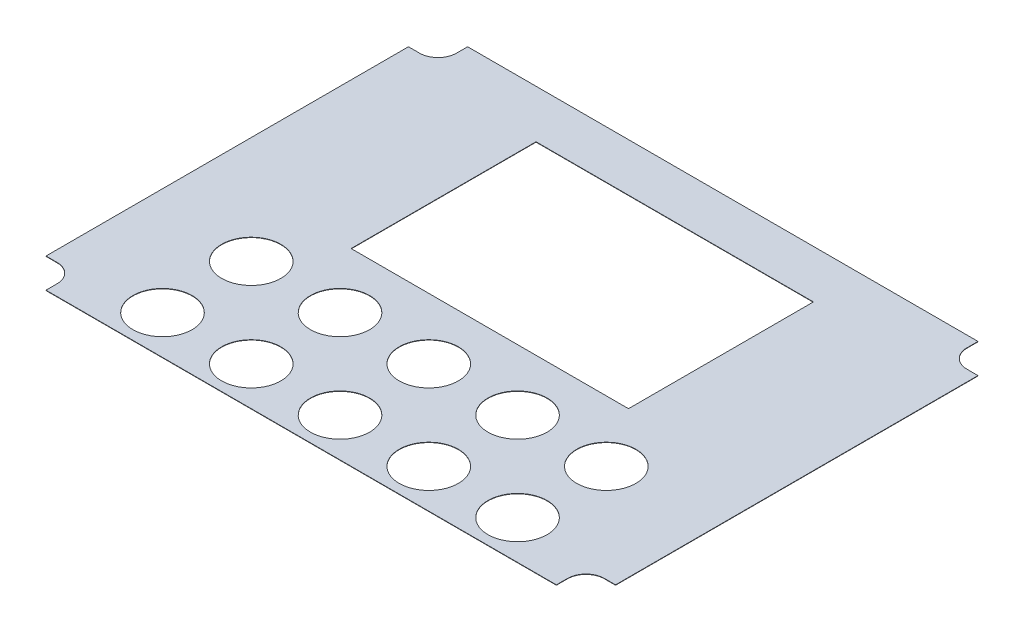
SolidWorks part; units mm, degrees
ref_plane "Front Plane" through (0, 0, 0) normal (0, 0, 1) x (1, 0, 0)
ref_plane "Top Plane" through (0, 0, 0) normal (0, 1, 0) x (1, 0, 0)
ref_plane "Right Plane" through (0, 0, 0) normal (1, 0, 0) x (0, 0, -1)
sketch "Sketch1" plane through (0, 0, 0) normal (0, 1, 0) x (1, 0, 0)
  line L1 (-77, 57) -> (77, 57)
  line L2 (-77, 57) -> (-77, -57)
  line L3 (-77, -57) -> (77, -57)
  line L4 (77, 57) -> (77, -57)
  line L5 (-77, 57) -> (77, -57) construction
  line L6 (-77, -57) -> (77, 57) construction
  point P0 (0, 0)
  dimension "D1" = 154
  dimension "D2" = 114
extrude "Boss-Extrude1" add sketch "Sketch1" along normal blind 0.1
sketch "Sketch2" plane through (0, 0.1, 0) normal (0, 1, 0) x (1, 0, 0)
  line L0 (-52.05, -19.4834) -> (-52.05, -25.5166)
  line L1 (-43.95, -19.4834) -> (-43.95, -25.5166)
  line L2 (-19.95, -19.4834) -> (-19.95, -25.5166)
  line L3 (-28.05, -19.4834) -> (-28.05, -25.5166)
  line L4 (4.05, -19.4834) -> (4.05, -25.5166)
  line L5 (-4.05, -19.4834) -> (-4.05, -25.5166)
  line L6 (28.05, -19.4834) -> (28.05, -25.5166)
  line L7 (19.95, -19.4834) -> (19.95, -25.5166)
  line L8 (52.05, -19.4834) -> (52.05, -25.5166)
  line L9 (43.95, -19.4834) -> (43.95, -25.5166)
  line L10 (-19.95, -43.4834) -> (-19.95, -49.5166)
  line L11 (-28.05, -43.4834) -> (-28.05, -49.5166)
  line L12 (4.05, -43.4834) -> (4.05, -49.5166)
  line L13 (-4.05, -43.4834) -> (-4.05, -49.5166)
  line L14 (28.05, -43.4834) -> (28.05, -49.5166)
  line L15 (19.95, -43.4834) -> (19.95, -49.5166)
  line L16 (52.05, -43.4834) -> (52.05, -49.5166)
  line L17 (43.95, -43.4834) -> (43.95, -49.5166)
  line L18 (-43.95, -43.4834) -> (-43.95, -49.5166)
  line L19 (-52.05, -43.4834) -> (-52.05, -49.5166)
  line L20 (-80.6235, 55.25) -> (97.5881, 55.25) construction
  line L21 (-86.1798, -55.25) -> (90.3856, -55.25) construction
  circle A0 centre (-60, 45) radius 3.5 construction
  circle A1 centre (60, 45) radius 3.5 construction
  circle A2 centre (-60, -45) radius 3.5 construction
  circle A3 centre (60, -45) radius 3.5 construction
  arc A4 (-52.05, -25.5166) -> (-43.95, -25.5166) centre (-48, -22.5) ccw
  arc A5 (-43.95, -19.4834) -> (-52.05, -19.4834) centre (-48, -22.5) ccw
  circle A6 centre (-48, -22.5) radius 8 construction
  circle A7 centre (-24, -22.5) radius 8 construction
  arc A8 (-28.05, -25.5166) -> (-19.95, -25.5166) centre (-24, -22.5) ccw
  arc A9 (-19.95, -19.4834) -> (-28.05, -19.4834) centre (-24, -22.5) ccw
  circle A10 centre (0, -22.5) radius 8 construction
  arc A11 (-4.05, -25.5166) -> (4.05, -25.5166) centre (0, -22.5) ccw
  arc A12 (4.05, -19.4834) -> (-4.05, -19.4834) centre (0, -22.5) ccw
  circle A13 centre (24, -22.5) radius 8 construction
  arc A14 (19.95, -25.5166) -> (28.05, -25.5166) centre (24, -22.5) ccw
  arc A15 (28.05, -19.4834) -> (19.95, -19.4834) centre (24, -22.5) ccw
  circle A16 centre (48, -22.5) radius 8 construction
  arc A17 (43.95, -25.5166) -> (52.05, -25.5166) centre (48, -22.5) ccw
  arc A18 (52.05, -19.4834) -> (43.95, -19.4834) centre (48, -22.5) ccw
  circle A19 centre (-24, -46.5) radius 8 construction
  arc A20 (-28.05, -49.5166) -> (-19.95, -49.5166) centre (-24, -46.5) ccw
  arc A21 (-19.95, -43.4834) -> (-28.05, -43.4834) centre (-24, -46.5) ccw
  circle A22 centre (0, -46.5) radius 8 construction
  arc A23 (-4.05, -49.5166) -> (4.05, -49.5166) centre (0, -46.5) ccw
  arc A24 (4.05, -43.4834) -> (-4.05, -43.4834) centre (0, -46.5) ccw
  circle A25 centre (24, -46.5) radius 8 construction
  arc A26 (19.95, -49.5166) -> (28.05, -49.5166) centre (24, -46.5) ccw
  arc A27 (28.05, -43.4834) -> (19.95, -43.4834) centre (24, -46.5) ccw
  circle A28 centre (48, -46.5) radius 8 construction
  arc A29 (43.95, -49.5166) -> (52.05, -49.5166) centre (48, -46.5) ccw
  arc A30 (52.05, -43.4834) -> (43.95, -43.4834) centre (48, -46.5) ccw
  circle A31 centre (-48, -46.5) radius 8 construction
  arc A32 (-52.05, -49.5166) -> (-43.95, -49.5166) centre (-48, -46.5) ccw
  arc A33 (-43.95, -43.4834) -> (-52.05, -43.4834) centre (-48, -46.5) ccw
  dimension "D1" = 7
  dimension "D8" = 10.1
  dimension "D9" = 16
  dimension "D2" = 60
  dimension "D3" = 45
  dimension "D4" = 45
  dimension "D5" = 60
  dimension "D6" = 8.1
  dimension "D7" = 4.05
  dimension "D10" = 48
  dimension "D11" = 110.5
  dimension "D12" = 55.25
  dimension "D13" = 22.5
extrude "Cut-Extrude1" cut sketch "Sketch2" against normal blind 3
sketch "Sketch3" plane through (0, 0.1, 0) normal (0, 1, 0) x (1, 0, 0)
  line L0 (77, 57) -> (-77, 57) construction
  line L1 (-37.5, 44) -> (37.5, 44)
  line L2 (-37.5, 44) -> (-37.5, -6)
  line L3 (-37.5, -6) -> (37.5, -6)
  line L4 (37.5, 44) -> (37.5, -6)
  line L6 (-77, 57) -> (-69, 57)
  line L7 (-77, 57) -> (-77, 49)
  line L8 (-77, 49) -> (-74, 49)
  line L9 (-69, 57) -> (-69, 54)
  line L10 (77, 57) -> (69, 57)
  line L11 (77, 57) -> (77, 49)
  line L12 (77, 49) -> (74, 49)
  line L13 (69, 57) -> (69, 54)
  line L14 (77, -57) -> (69, -57)
  line L15 (77, -57) -> (77, -49)
  line L16 (77, -49) -> (74, -49)
  line L17 (69, -57) -> (69, -54)
  line L18 (-77, -57) -> (-69, -57)
  line L19 (-77, -57) -> (-77, -49)
  line L20 (-77, -49) -> (-74, -49)
  line L21 (-69, -57) -> (-69, -54)
  circle A0 centre (-48, -22.5) radius 8
  circle A1 centre (-24, -22.5) radius 8
  circle A2 centre (0, -22.5) radius 8
  circle A3 centre (24, -22.5) radius 8
  circle A4 centre (48, -22.5) radius 8
  circle A5 centre (-24, -46.5) radius 8
  circle A6 centre (0, -46.5) radius 8
  circle A7 centre (24, -46.5) radius 8
  circle A8 centre (48, -46.5) radius 8
  circle A9 centre (-48, -46.5) radius 8
  arc A10 (-69, -54) -> (-74, -49) centre (-74, -54) ccw
  arc A11 (69, -54) -> (74, -49) centre (74, -54) cw
  arc A12 (74, 49) -> (69, 54) centre (74, 54) cw
  arc A13 (-74, 49) -> (-69, 54) centre (-74, 54) ccw
  point P50 (-69, -49)
  point P53 (69, -49)
  point P56 (69, 49)
  point P59 (-69, 49)
  arc M1 (-52.05, -43.4834) -> (-43.95, -43.4834) centre (-48, -46.5) cw
  line M2 (-43.95, -43.4834) -> (-43.95, -49.5166)
  arc M3 (-43.95, -49.5166) -> (-52.05, -49.5166) centre (-48, -46.5) cw
  line M4 (-52.05, -49.5166) -> (-52.05, -43.4834)
  arc M5 (43.95, -43.4834) -> (52.05, -43.4834) centre (48, -46.5) cw
  line M6 (52.05, -43.4834) -> (52.05, -49.5166)
  arc M7 (52.05, -49.5166) -> (43.95, -49.5166) centre (48, -46.5) cw
  line M8 (43.95, -49.5166) -> (43.95, -43.4834)
  arc M9 (19.95, -43.4834) -> (28.05, -43.4834) centre (24, -46.5) cw
  line M10 (28.05, -43.4834) -> (28.05, -49.5166)
  arc M11 (28.05, -49.5166) -> (19.95, -49.5166) centre (24, -46.5) cw
  line M12 (19.95, -49.5166) -> (19.95, -43.4834)
  arc M13 (-4.05, -43.4834) -> (4.05, -43.4834) centre (0, -46.5) cw
  line M14 (4.05, -43.4834) -> (4.05, -49.5166)
  arc M15 (4.05, -49.5166) -> (-4.05, -49.5166) centre (0, -46.5) cw
  line M16 (-4.05, -49.5166) -> (-4.05, -43.4834)
  arc M17 (-28.05, -43.4834) -> (-19.95, -43.4834) centre (-24, -46.5) cw
  line M18 (-19.95, -43.4834) -> (-19.95, -49.5166)
  arc M19 (-19.95, -49.5166) -> (-28.05, -49.5166) centre (-24, -46.5) cw
  line M20 (-28.05, -49.5166) -> (-28.05, -43.4834)
  arc M21 (43.95, -19.4834) -> (52.05, -19.4834) centre (48, -22.5) cw
  line M22 (52.05, -19.4834) -> (52.05, -25.5166)
  arc M23 (52.05, -25.5166) -> (43.95, -25.5166) centre (48, -22.5) cw
  line M24 (43.95, -25.5166) -> (43.95, -19.4834)
  arc M25 (19.95, -19.4834) -> (28.05, -19.4834) centre (24, -22.5) cw
  line M26 (28.05, -19.4834) -> (28.05, -25.5166)
  arc M27 (28.05, -25.5166) -> (19.95, -25.5166) centre (24, -22.5) cw
  line M28 (19.95, -25.5166) -> (19.95, -19.4834)
  arc M29 (-4.05, -19.4834) -> (4.05, -19.4834) centre (0, -22.5) cw
  line M30 (4.05, -19.4834) -> (4.05, -25.5166)
  arc M31 (4.05, -25.5166) -> (-4.05, -25.5166) centre (0, -22.5) cw
  line M32 (-4.05, -25.5166) -> (-4.05, -19.4834)
  arc M33 (-28.05, -19.4834) -> (-19.95, -19.4834) centre (-24, -22.5) cw
  line M34 (-19.95, -19.4834) -> (-19.95, -25.5166)
  arc M35 (-19.95, -25.5166) -> (-28.05, -25.5166) centre (-24, -22.5) cw
  line M36 (-28.05, -25.5166) -> (-28.05, -19.4834)
  arc M37 (-52.05, -19.4834) -> (-43.95, -19.4834) centre (-48, -22.5) cw
  line M38 (-43.95, -19.4834) -> (-43.95, -25.5166)
  arc M39 (-43.95, -25.5166) -> (-52.05, -25.5166) centre (-48, -22.5) cw
  line M40 (-52.05, -25.5166) -> (-52.05, -19.4834)
  line M41 (77, -57) -> (77, 57)
  line M42 (77, 57) -> (-77, 57)
  line M43 (-77, 57) -> (-77, -57)
  line M44 (-77, -57) -> (77, -57)
  dimension "D1" = 16
  dimension "D16" = 5
  dimension "D4" = 75
  dimension "D5" = 50
  dimension "D6" = 13
  dimension "D7" = 37.5
  dimension "D8" = 8
  dimension "D9" = 8
  dimension "D10" = 8
  dimension "D11" = 8
  dimension "D12" = 8
  dimension "D13" = 8
  dimension "D14" = 8
  dimension "D15" = 8
  dimension "D2" = 5
  dimension "D3" = 2
extrude "Cut-Extrude2" cut sketch "Sketch3" against normal blind 1 contours L8 A13 L9 M42 M43 | A12 L12 L13 M41 M42 | A11 L17 L16 M44 M41 | L21 A10 L20 M43 M44 | A0 M40 M37 M38 M39 | A1 M36 M33 M34 M35 | A2 M32 M29 M30 M31 | A3 M28 M25 M26 M27 | A4 M24 M21 M22 M23 | A8 M8 M5 M6 M7 | A7 M12 M9 M10 M11 | A6 M16 M13 M14 M15 | A5 M20 M17 M18 M19 | A9 M4 M1 M2 M3 | L4 L1 L2 L3
